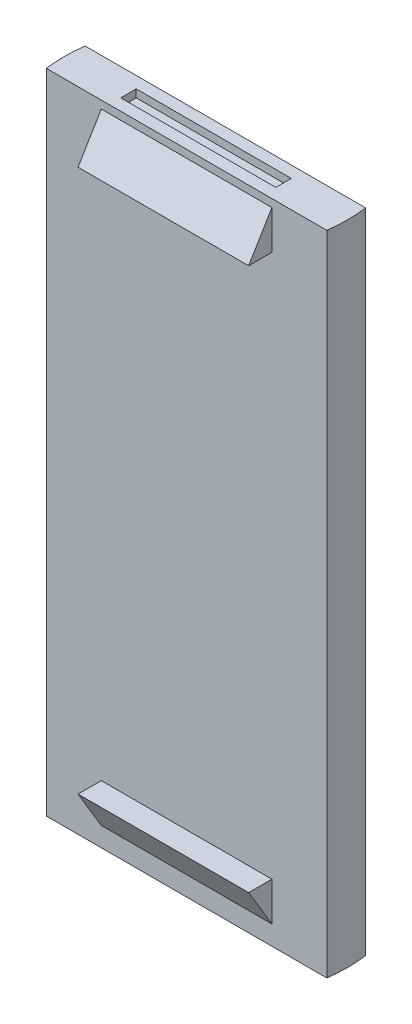
SolidWorks part; units mm, degrees
ref_plane "Front Plane" through (0, 0, 0) normal (0, 0, 1) x (1, 0, 0)
ref_plane "Top Plane" through (0, 0, 0) normal (0, 1, 0) x (1, 0, 0)
ref_plane "Right Plane" through (0, 0, 0) normal (1, 0, 0) x (0, 0, -1)
sketch "Sketch1" plane through (0, 0, 0) normal (0, 0, 1) x (1, 0, 0)
  line L1 (49.53, -180.34) -> (-49.53, -180.34)
  line L2 (49.53, -180.34) -> (49.53, 180.34)
  line L3 (49.53, 180.34) -> (-49.53, 180.34)
  line L4 (-49.53, -180.34) -> (-49.53, 180.34)
  line L5 (49.53, -180.34) -> (-49.53, 180.34) construction
  line L6 (49.53, 180.34) -> (-49.53, -180.34) construction
  point P0 (0, 0)
  dimension "D1" = 360.68
  dimension "D2" = 99.06
extrude "Boss-Extrude1" add sketch "Sketch1" along normal blind 12.7
sketch "Sketch2" plane through (0, 0, 12.7) normal (0, 0, 1) x (1, 0, 0)
  line L0 (0, 180.34) -> (0, -230.2299) construction
  line L2 (49.53, 180.34) -> (-49.53, 180.34) construction
  line L4 (-49.53, 0) -> (49.53, 0) construction
  line L10 (27.94, -25.4) -> (-27.94, -25.4)
  line L15 (27.94, -25.4) -> (27.94, 177.8)
  line L16 (27.94, 177.8) -> (-27.94, 177.8)
  line L17 (49.53, -180.34) -> (49.53, 180.34) construction
  line L18 (-27.94, -25.4) -> (-27.94, 177.8)
  line L19 (27.94, -25.4) -> (-27.94, 177.8) construction
  line L20 (27.94, 177.8) -> (-27.94, -25.4) construction
  line L21 (27.94, -12.7) -> (-27.94, -12.7)
  line L22 (27.94, -12.7) -> (27.94, 165.1)
  line L23 (27.94, 165.1) -> (-27.94, 165.1)
  line L24 (-27.94, -12.7) -> (-27.94, 165.1)
  line L25 (27.94, -12.7) -> (-27.94, 165.1) construction
  line L26 (27.94, 165.1) -> (-27.94, -12.7) construction
  point P1 (0, 76.2)
  point P15 (0, 76.2)
  dimension "D1" = 76.2
  dimension "D2" = 203.2
  dimension "D3" = 177.8
  dimension "D4" = 55.88
sketch "Sketch3" plane through (0, 0, 0) normal (0, 0, -1) x (-1, 0, 0)
  line L0 (0, -180.34) -> (0, 180.34) construction
  line L1 (-49.53, 180.34) -> (49.53, 180.34) construction
  line L2 (49.53, 0) -> (-49.53, 0) construction
  line L3 (-49.53, -180.34) -> (-49.53, 180.34) construction
  line L11 (16.002, -165.1) -> (-16.002, -165.1)
  line L12 (16.002, -165.1) -> (16.002, -38.1)
  line L13 (16.002, -38.1) -> (-16.002, -38.1)
  line L14 (-16.002, -165.1) -> (-16.002, -38.1)
  line L15 (16.002, -165.1) -> (-16.002, -38.1) construction
  line L16 (16.002, -38.1) -> (-16.002, -165.1) construction
  line L23 (16.002, -153.67) -> (-16.002, -153.67)
  line L24 (16.002, -153.67) -> (16.002, -49.53)
  line L25 (16.002, -49.53) -> (-16.002, -49.53)
  line L26 (-16.002, -153.67) -> (-16.002, -49.53)
  line L27 (16.002, -153.67) -> (-16.002, -49.53) construction
  line L28 (16.002, -49.53) -> (-16.002, -153.67) construction
  point P6 (0, 0)
  point P12 (0, 0)
  point P17 (0, -101.6)
  point P26 (0, -101.6)
  dimension "D1" = 127
  dimension "D2" = 32.004
  dimension "D5" = 101.6
  dimension "D7" = 104.14
extrude "Boss-Extrude3" add sketch "Sketch3" along normal blind 20.32 contours L25 L12 L13 L14 | L12 L23 L14 L11
extrude "Boss-Extrude4" add sketch "Sketch2" along normal mid plane 15.24 contours L23 L15 L16 L18 | L15 L21 L18 L10
ref_plane "Plane2" through (0, 0, 6.35) normal (0, 0, 1) x (1, 0, 0)
mirror "Mirror1" about plane through (0, 0, 6.35) normal (0, 0, 1) of "Boss-Extrude3"
sketch "Sketch5" plane through (0, 0, 0) normal (1, 0, 0) x (0, 0, -1)
  line L0 (-12.7, -180.34) -> (0, -180.34) construction
  line L1 (-12.7, 180.34) -> (0, 180.34) construction
  line L2 (-12.7, 180.34) -> (-12.7, -180.34) construction
  line L3 (-12.7, -180.34) -> (0, -180.34) construction
  line L5 (-20.32, 165.1) -> (-12.7, 165.1) construction
  line L6 (20.32, -153.67) -> (0, -153.67) construction
  line L7 (20.32, -153.67) -> (20.32, -165.1) construction
  line L8 (20.32, -165.1) -> (0, -165.1) construction
  line L9 (0, -153.67) -> (0, -165.1) construction
  line L10 (-33.02, -153.67) -> (-12.7, -153.67) construction
  line L11 (-33.02, -153.67) -> (-33.02, -165.1) construction
  line L12 (-33.02, -165.1) -> (-12.7, -165.1) construction
  line L13 (-12.7, -153.67) -> (-12.7, -165.1) construction
  line L14 (20.32, -38.1) -> (0, -38.1) construction
  line L15 (20.32, -38.1) -> (20.32, -49.53) construction
  line L16 (20.32, -49.53) -> (0, -49.53) construction
  line L17 (0, -38.1) -> (0, -49.53) construction
  line L18 (-33.02, -38.1) -> (-12.7, -38.1) construction
  line L19 (-33.02, -38.1) -> (-33.02, -49.53) construction
  line L20 (-33.02, -49.53) -> (-12.7, -49.53) construction
  line L21 (-12.7, -38.1) -> (-12.7, -49.53) construction
  line L25 (-12.7, -12.7) -> (-12.7, 0) construction
  line L26 (-20.32, 177.8) -> (-12.7, 177.8) construction
  line L27 (-20.32, 177.8) -> (-20.32, 165.1) construction
  line L28 (-20.32, 165.1) -> (-12.7, 165.1) construction
  line L29 (-12.7, 177.8) -> (-12.7, 165.1) construction
  line L30 (0, 180.34) -> (0, -180.34) construction
  line L31 (20.32, -153.67) -> (0, -165.1)
  line L32 (0, -165.1) -> (20.32, -165.1)
  line L33 (20.32, -165.1) -> (20.32, -153.67)
  line L34 (-33.02, -153.67) -> (-12.7, -165.1)
  line L35 (-12.7, -165.1) -> (-33.02, -165.1)
  line L36 (-33.02, -165.1) -> (-33.02, -153.67)
  line L37 (-33.02, -49.53) -> (-33.02, -38.1)
  line L38 (-33.02, -38.1) -> (-12.7, -38.1)
  line L39 (-12.7, -38.1) -> (-33.02, -49.53)
  line L40 (20.32, -49.53) -> (0, -38.1)
  line L41 (0, -38.1) -> (20.32, -38.1)
  line L42 (20.32, -38.1) -> (20.32, -49.53)
  line L46 (-12.7, 177.8) -> (-20.32, 165.1)
  line L47 (-20.32, 165.1) -> (-20.32, 177.8)
  line L48 (-20.32, 177.8) -> (-12.7, 177.8)
  line L49 (-12.7, -12.7) -> (-20.32, -12.7) construction
  line L50 (-20.32, -12.7) -> (-20.32, -25.4) construction
  line L51 (-20.32, -25.4) -> (-12.7, -25.4) construction
  line L52 (-20.32, -12.7) -> (-12.7, -25.4)
  line L53 (-12.7, -25.4) -> (-20.32, -25.4)
  line L54 (-20.32, -25.4) -> (-20.32, -12.7)
extrude "Cut-Extrude2" cut sketch "Sketch5" against normal mid plane 76.2
sketch "Sketch6" plane through (0, 180.34, 0) normal (0, 1, 0) x (1, 0, 0)
  line L0 (0, 0) -> (0, -12.7) construction
  line L1 (-49.53, -12.7) -> (49.53, -12.7) construction
  line L2 (-49.53, -12.7) -> (-49.53, 0) construction
  line L3 (-49.53, 0) -> (49.53, 0) construction
  line L4 (49.53, -12.7) -> (49.53, 0) construction
  line L5 (-49.53, -6.35) -> (49.53, -6.35) construction
  line L7 (25.4, -8.89) -> (-25.4, -8.89)
  line L8 (25.4, -8.89) -> (25.4, -3.81)
  line L9 (25.4, -3.81) -> (-25.4, -3.81)
  line L10 (-25.4, -8.89) -> (-25.4, -3.81)
  line L11 (25.4, -8.89) -> (-25.4, -3.81) construction
  line L12 (25.4, -3.81) -> (-25.4, -8.89) construction
  point P10 (0, -6.35)
  dimension "D1" = 5.08
  dimension "D2" = 50.8
extrude "Cut-Extrude3" cut sketch "Sketch6" against normal blind 2.54
mirror "Mirror2" about plane through (0, 0, 0) normal (0, 1, 0) of "Cut-Extrude3"
sketch "Sketch7" plane through (0, 180.34, 0) normal (0, 1, 0) x (1, 0, 0)
  line L0 (-49.53, -6.35) -> (49.53, -6.35) construction
  line L1 (-49.53, -12.7) -> (-49.53, 0) construction
  line L2 (49.53, -12.7) -> (49.53, 0) construction
  line L3 (0, 0) -> (0, -12.7) construction
  line L4 (-16.002, 0) -> (16.002, 0) construction
  line L5 (-27.94, -12.7) -> (27.94, -12.7) construction
  circle A0 centre (0, -6.35) radius 46.355
  circle A1 centre (0, -6.35) radius 50.8
  dimension "D1" = 92.71
  dimension "D2" = 101.6
extrude "Cut-Extrude4" cut sketch "Sketch7" against normal through all
sketch "Sketch8" plane through (0, 0, 0) normal (0, 0, 1) x (1, 0, 0)
  line L0 (-27.94, -25.4) -> (27.94, -25.4) construction
  line L1 (79.329, -31.75) -> (-78.9914, -31.75)
  line L2 (79.329, -31.75) -> (79.329, -194.8889)
  line L3 (79.329, -194.8889) -> (-78.9914, -194.8889)
  line L4 (-78.9914, -31.75) -> (-78.9914, -194.8889)
  dimension "D1" = 6.35
extrude "Cut-Extrude5" cut sketch "Sketch8" against normal through all both and the other way through all
